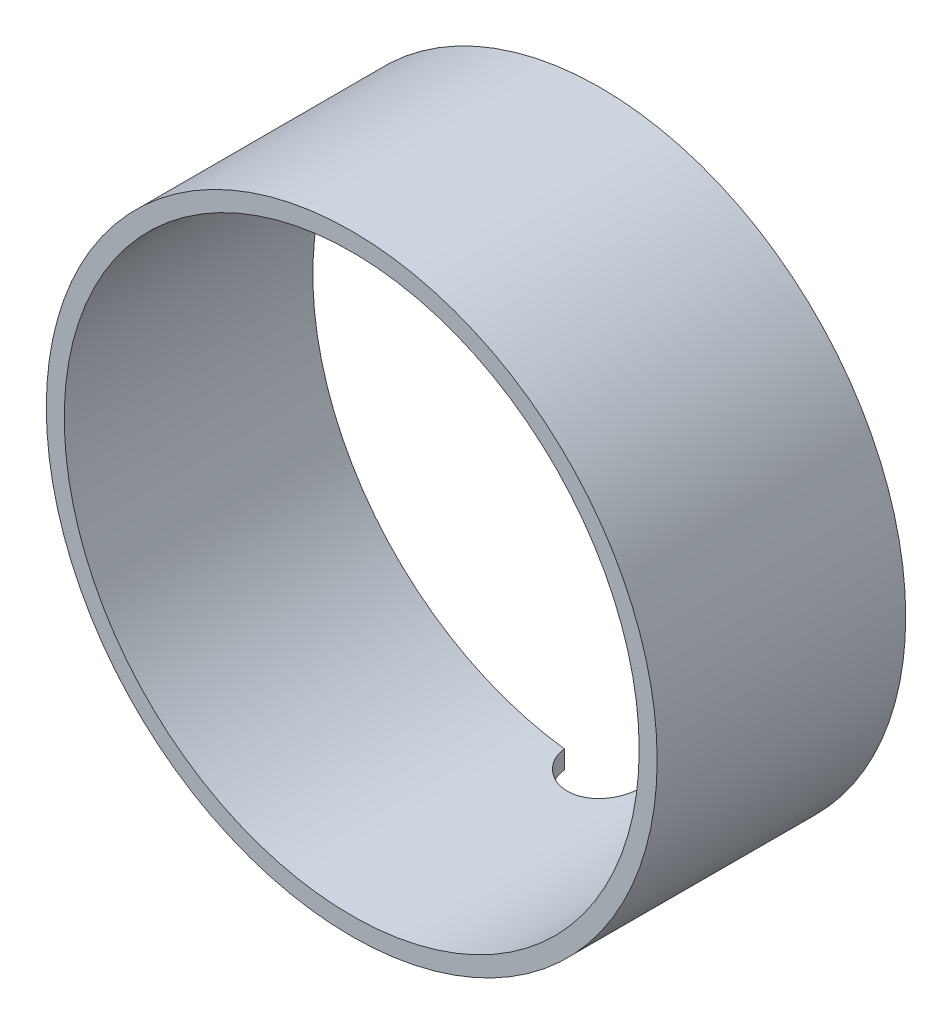
SolidWorks part; units mm, degrees
ref_plane "front" through (0, 0, 0) normal (0, 0, 1) x (1, 0, 0)
ref_plane "top" through (0, 0, 0) normal (0, 1, 0) x (1, 0, 0)
ref_plane "right" through (0, 0, 0) normal (1, 0, 0) x (0, 0, -1)
sketch "Sketch1" plane through (0, 0, 0) normal (0, 0, 1) x (1, 0, 0)
  circle A0 centre (0, 0) radius 161.925
  circle A1 centre (0, 0) radius 152.4
  dimension "D2" = 323.85
  dimension "D3" = 9.525
extrude "Base-Extrude" add sketch "Sketch1" against normal blind 131.7625
sketch "Sketch2" plane through (0, 0, 0) normal (1, 0, 0) x (0, 0, -1)
  line L0 (0, 0) -> (271.4625, 0) construction
  line L1 (131.7625, 0) -> (0, 0) construction
  line L2 (131.7625, -161.925) -> (131.7625, 161.925) construction
  point P5 (131.7625, 0)
  dimension "D1" = 139.7
ref_plane "Plane1" through (0, 0, -271.4625) normal (0, 0, -1) x (-1, 0, 0)
sketch "Sketch3" plane through (0, 0, 0) normal (0, 1, 0) x (1, 0, 0)
  circle A0 centre (0, 133.35) radius 19.05
  dimension "D1" = 19.05
  dimension "D2" = 133.35
extrude "Cut-Extrude1" cut sketch "Sketch3" against normal through all
